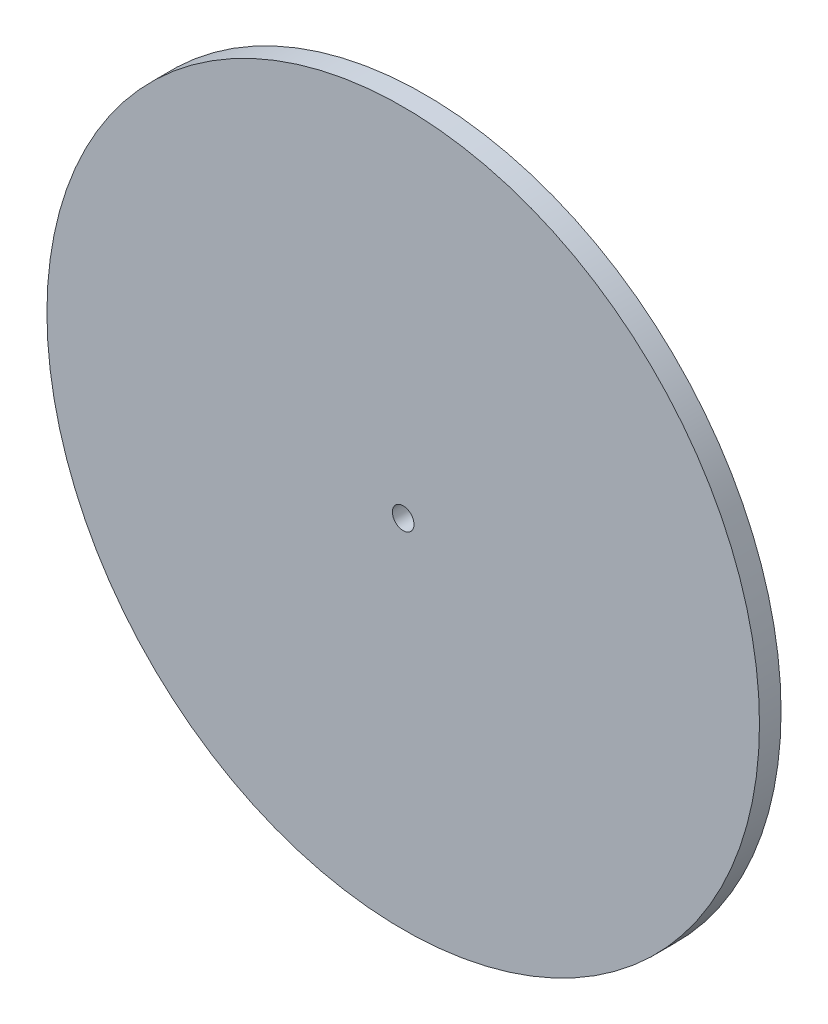
SolidWorks part; units mm, degrees
material "AISI 304"
ref_plane "Front Plane" through (0, 0, 0) normal (0, 0, 1) x (1, 0, 0)
ref_plane "Top Plane" through (0, 0, 0) normal (0, 1, 0) x (1, 0, 0)
ref_plane "Right Plane" through (0, 0, 0) normal (1, 0, 0) x (0, 0, -1)
sketch "Sketch1" plane through (0, 0, 0) normal (0, 0, 1) x (1, 0, 0)
  line L1 (152.6517, 233.2966) -> (91.7092, 154.0094) construction
  line L2 (153.9172, 91.8015) -> (233.2547, 152.6793) construction
  line L3 (-56.8564, 273.6013) -> (-43.8847, 174.4439)
  line L4 (44.0906, 174.4439) -> (57.1436, 273.5912)
  line L5 (-56.8564, 273.6013) -> (-43.8847, 174.4439) construction
  line L6 (44.0906, 174.4439) -> (57.1436, 273.5912) construction
  line L7 (272.2966, 56.6523) -> (173.1392, 43.6806) construction
  line L8 (173.1392, -44.2947) -> (272.2864, -57.3477) construction
  line L9 (231.9919, -152.8558) -> (152.7047, -91.9133) construction
  line L10 (90.4967, -154.1212) -> (151.3746, -233.4588) construction
  line L11 (55.3476, -272.5007) -> (42.3759, -173.3433) construction
  line L12 (-45.5994, -173.3433) -> (-58.6524, -272.4905) construction
  line L13 (-154.1605, -232.196) -> (-93.218, -152.9087) construction
  line L14 (-155.426, -90.7008) -> (-234.7635, -151.5786) construction
  line L15 (-273.8054, -55.5517) -> (-174.648, -42.58) construction
  line L16 (-174.648, 45.3953) -> (-273.7952, 58.4483) construction
  line L17 (-233.5007, 153.9564) -> (-154.2135, 93.014) construction
  line L18 (-92.0055, 155.2219) -> (-152.8834, 234.5594) construction
  circle A1 centre (0, 0) radius 5
  circle A2 centre (0, 0) radius 165
  arc A3 (233.2547, 152.6793) -> (152.6517, 233.2966) centre (-129.8378, -129.7456) ccw construction
  arc A4 (153.9172, 91.8015) -> (91.7092, 154.0094) centre (-129.8378, -129.7456) ccw construction
  arc A5 (57.1436, 273.5912) -> (-56.8564, 273.6013) centre (0.103, -182.8586) ccw
  arc A6 (44.0906, 174.4439) -> (-43.8847, 174.4439) centre (0.103, -182.8586) ccw
  arc A7 (57.1436, 273.5912) -> (-56.8564, 273.6013) centre (0.103, -182.8586) ccw construction
  arc A8 (44.0906, 174.4439) -> (-43.8847, 174.4439) centre (0.103, -182.8586) ccw construction
  arc A9 (272.2864, -57.3477) -> (272.2966, 56.6523) centre (-184.1633, -0.307) ccw construction
  arc A10 (173.1392, -44.2947) -> (173.1392, 43.6806) centre (-184.1633, -0.307) ccw construction
  arc A11 (151.3746, -233.4588) -> (231.9919, -152.8558) centre (-131.0503, 129.6338) ccw construction
  arc A12 (90.4967, -154.1212) -> (152.7047, -91.9133) centre (-131.0503, 129.6338) ccw construction
  arc A13 (-58.6524, -272.4905) -> (55.3476, -272.5007) centre (-1.6118, 183.9592) ccw construction
  arc A14 (-45.5994, -173.3433) -> (42.3759, -173.3433) centre (-1.6118, 183.9592) ccw construction
  arc A15 (-234.7635, -151.5786) -> (-154.1605, -232.196) centre (128.329, 130.8463) ccw construction
  arc A16 (-155.426, -90.7008) -> (-93.218, -152.9087) centre (128.329, 130.8463) ccw construction
  arc A17 (-273.7952, 58.4483) -> (-273.8054, -55.5517) centre (182.6545, 1.4077) ccw construction
  arc A18 (-174.648, 45.3953) -> (-174.648, -42.58) centre (182.6545, 1.4077) ccw construction
  arc A19 (-152.8834, 234.5594) -> (-233.5007, 153.9564) centre (129.5415, -128.5331) ccw construction
  arc A20 (-92.0055, 155.2219) -> (-154.2135, 93.014) centre (129.5415, -128.5331) ccw construction
  point P54 (-0.7544, 0.5503)
  dimension "D1" = 330
  dimension "D2" = 10
  dimension "D3" = 0
  dimension "D4" = 8
extrude "Boss-Extrude1" add sketch "Sketch1" along normal blind 10
